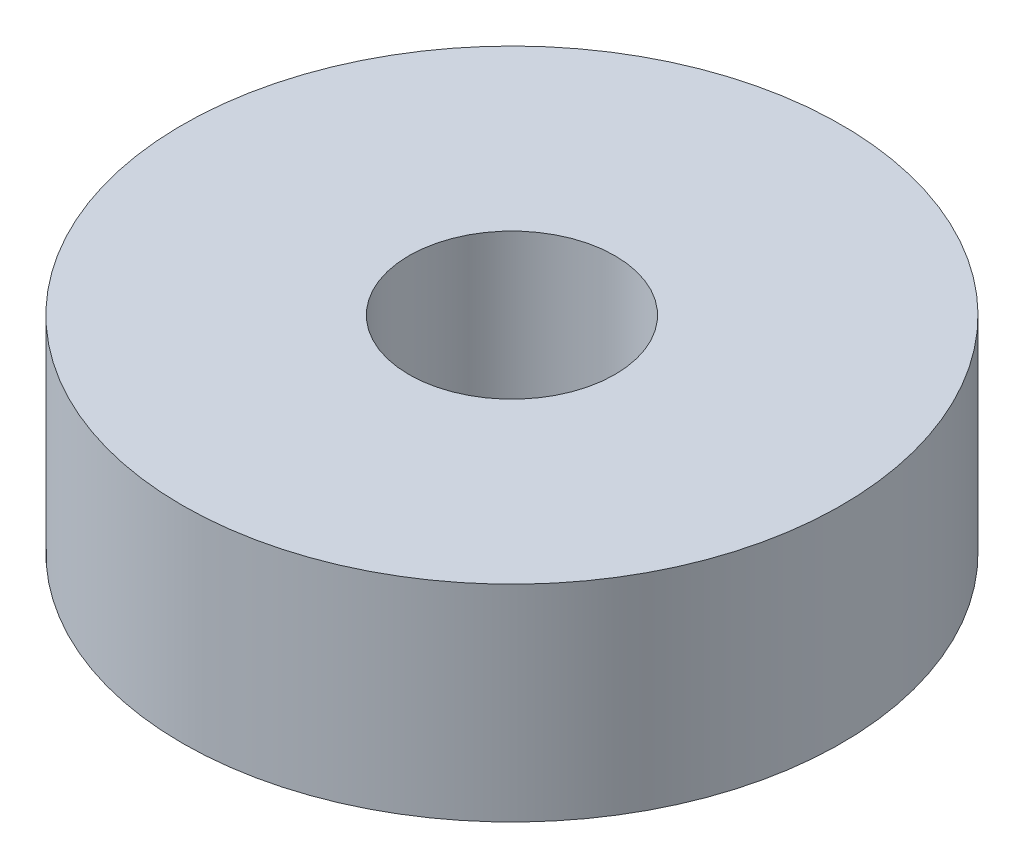
SolidWorks part; units mm, degrees
ref_plane "Płaszczyzna przednia" through (0, 0, 0) normal (0, 0, 1) x (1, 0, 0)
ref_plane "Płaszczyzna górna" through (0, 0, 0) normal (0, 1, 0) x (1, 0, 0)
ref_plane "Płaszczyzna prawa" through (0, 0, 0) normal (1, 0, 0) x (0, 0, -1)
sketch "Szkic1" plane through (0, 0, 0) normal (0, 1, 0) x (1, 0, 0)
  circle A0 centre (0, 0) radius 8
  circle A1 centre (0, 0) radius 2.5
  dimension "D1" = 16
  dimension "D2" = 5
extrude "Dodanie-wyciągnięcie1" add sketch "Szkic1" along normal blind 5
